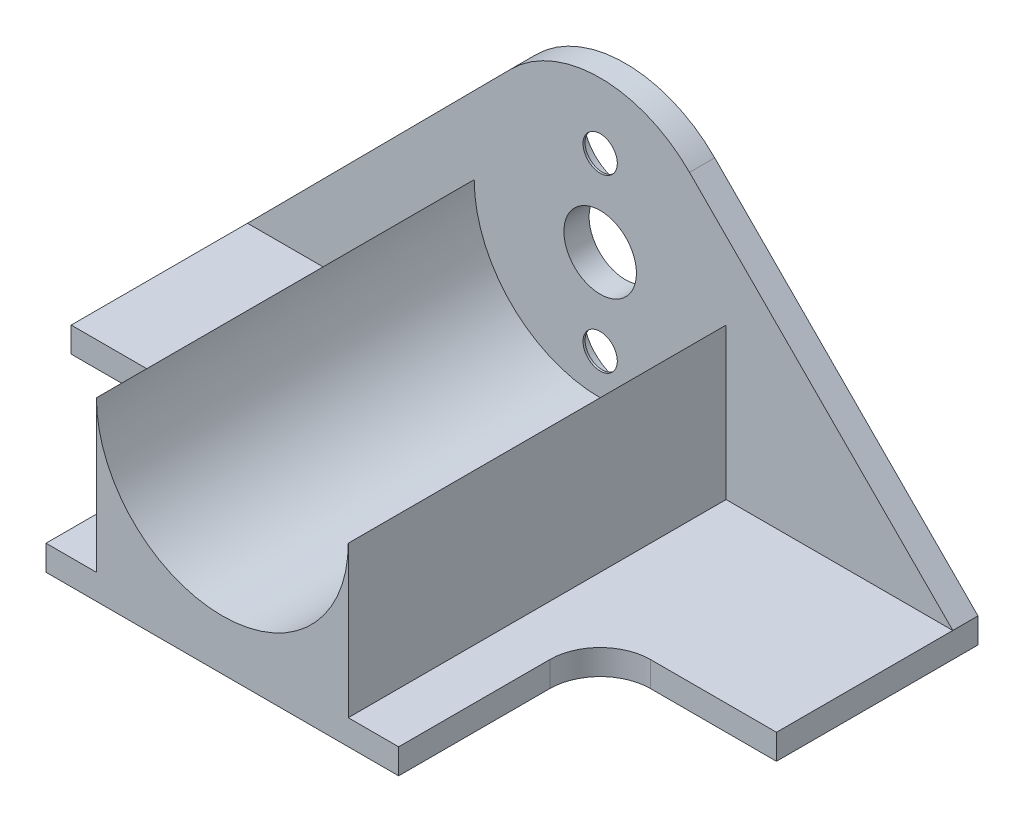
SolidWorks part; units mm, degrees
ref_plane "Front Plane" through (0, 0, 0) normal (0, 0, 1) x (1, 0, 0)
ref_plane "Top Plane" through (0, 0, 0) normal (0, 1, 0) x (1, 0, 0)
ref_plane "Right Plane" through (0, 0, 0) normal (1, 0, 0) x (0, 0, -1)
sketch "Sketch2" plane through (0, 0, 0) normal (0, 1, 0) x (1, 0, 0)
  line L0 (-17.5, -30) -> (17.5, -30)
  line L1 (-35, -10) -> (-17.5, -10)
  line L2 (-35, -10) -> (-35, 10)
  line L3 (-35, 10) -> (35, 10)
  line L4 (35, -10) -> (35, 10)
  line L5 (-35, -10) -> (35, 10) construction
  line L6 (-35, 10) -> (35, -10) construction
  line L7 (0, -23.3039) -> (0, -30)
  line L8 (17.5, -30) -> (17.5, -10)
  line L9 (-17.5, -30) -> (-17.5, -10)
  line L10 (17.5, -10) -> (35, -10)
  line L11 (-17.5, -10) -> (17.5, -10) construction
  point P0 (0, 0)
  dimension "D1" = 70
  dimension "D2" = 20
  dimension "2" = 20
  dimension "3.5" = 35
extrude "Boss-Extrude1" add sketch "Sketch2" along normal blind 2.5
fillet "Fillet1" radius 5 2 edges at (-17.5, 1.25, 10) (17.5, 1.25, 10)
sketch "Sketch3" plane through (0, 2.5, 0) normal (0, 1, 0) x (1, 0, 0)
  line L0 (35, -10) -> (35, 10) construction
  line L1 (-35, 10) -> (35, 10)
  line L2 (-35, 10) -> (-35, 7.5)
  line L3 (-35, 7.5) -> (35, 7.5)
  line L4 (35, 10) -> (35, 7.5)
  dimension "D1" = 2.5
extrude "Boss-Extrude2" add sketch "Sketch3" along normal blind 30
sketch "Sketch4" plane through (0, 0, -7.5) normal (0, 0, 1) x (1, 0, 0)
  line L0 (-35, 32.5) -> (35, 32.5) construction
  line L1 (0, 32.5) -> (0, 2.5) construction
  line L2 (-35, 2.5) -> (35, 2.5) construction
  line L3 (-35, 2.5) -> (-8.8687, 28.8089)
  line L4 (35, 2.5) -> (8.8687, 28.8089)
  line L5 (-35, 2.5) -> (-35, 32.5)
  line L6 (-35, 32.5) -> (35, 32.5)
  line L7 (35, 32.5) -> (35, 2.5)
  arc A0 (8.8687, 28.8089) -> (-8.8687, 28.8089) centre (0, 20) ccw
  line M6 (35, 2.5) -> (35, 32.5)
  line M7 (35, 32.5) -> (-35, 32.5)
  line M8 (-35, 32.5) -> (-35, 2.5)
  dimension "D1" = 25
extrude "Cut-Extrude1" cut sketch "Sketch4" against normal up to next contours A0 L6 L3 M8 | A0 L4 M6 M7
sketch "Sketch6" plane through (0, 0, -7.5) normal (0, 0, 1) x (1, 0, 0)
  line L0 (0, 2.5) -> (0, 32.5) construction
  line L1 (-35, 2.5) -> (35, 2.5) construction
  circle A0 centre (0, 17.5) radius 12.5
  arc A1 (8.8687, 28.8089) -> (-8.8687, 28.8089) centre (0, 20) ccw construction
  point P9 (-14.9357, 19.6607)
  point P10 (0, 0)
  point P11 (0, 12.128)
  point P12 (0, 17.6683)
  point P13 (0, -7.7194)
  point P14 (0, 17.5)
  dimension "D1" = 25
sketch "Sketch7" plane through (0, 0, -7.5) normal (0, 0, 1) x (1, 0, 0)
  line L0 (12.5, 17.5) -> (12.5, 2.5)
  line L1 (-35, 2.5) -> (35, 2.5) construction
  line L2 (-12.5, 2.5) -> (12.5, 2.5)
  line L3 (-12.5, 17.5) -> (-12.5, 2.5)
  circle A0 centre (0, 17.5) radius 12.5 construction
  arc A1 (-12.5, 17.5) -> (12.5, 17.5) centre (0, 17.5) ccw
  point P7 (16.8358, 2.5)
extrude "Boss-Extrude3" add sketch "Sketch7" along normal up to surface (37.5 mm away) up to face at (0, 1.25, 30)
sketch "Sketch10" plane through (0, 0, -7.5) normal (0, 0, 1) x (1, 0, 0)
  circle A0 centre (0, 17.5) radius 3.6
  dimension "D1" = 7.2
extrude "Cut-Extrude3" cut sketch "Sketch10" against normal up to next
sketch "Sketch11" plane through (0, 0, -10) normal (0, 0, -1) x (-1, 0, 0)
  line L0 (0, 9) -> (0, 26) construction
  circle A0 centre (0, 17.5) radius 12.5 construction
  circle A1 centre (0, 17.5) radius 12.5 construction
  point P7 (0, 17.5)
  dimension "D1" = 17
hole_wizard "CBORE for M3 Hex Head Machine Screw1" positions "Sketch12" profile "Sketch13" counterbore size "M3" standard "ANSI Metric" end condition through all
sketch "Sketch12" plane through (0, 0, -10) normal (0, 0, -1) x (-1, 0, 0)
  point P0 (0, 26)
  point P3 (0, 9)
sketch "Sketch13" plane through (0, 26, -10) normal (1, 0, 0) x (0, 1, 0)
  line L0 (0, 0) -> (0, 40)
  line L1 (0, 40) -> (1.7, 40)
  line L3 (1.7, 40) -> (1.7, 2.3)
  line L4 (1.7, 2.3) -> (4.2, 2.3)
  line L5 (4.2, 2.3) -> (4.2, 0)
  line L7 (4.2, 0) -> (0, 0)
  line L11 (0, -6.35) -> (0, 107.95) construction
  dimension "Thru Hole Dia." = 3.4
  dimension "Thru Hole Depth" = 40
  dimension "C'Bore Dia." = 8.4
  dimension "C'Bore Depth" = 2.3
